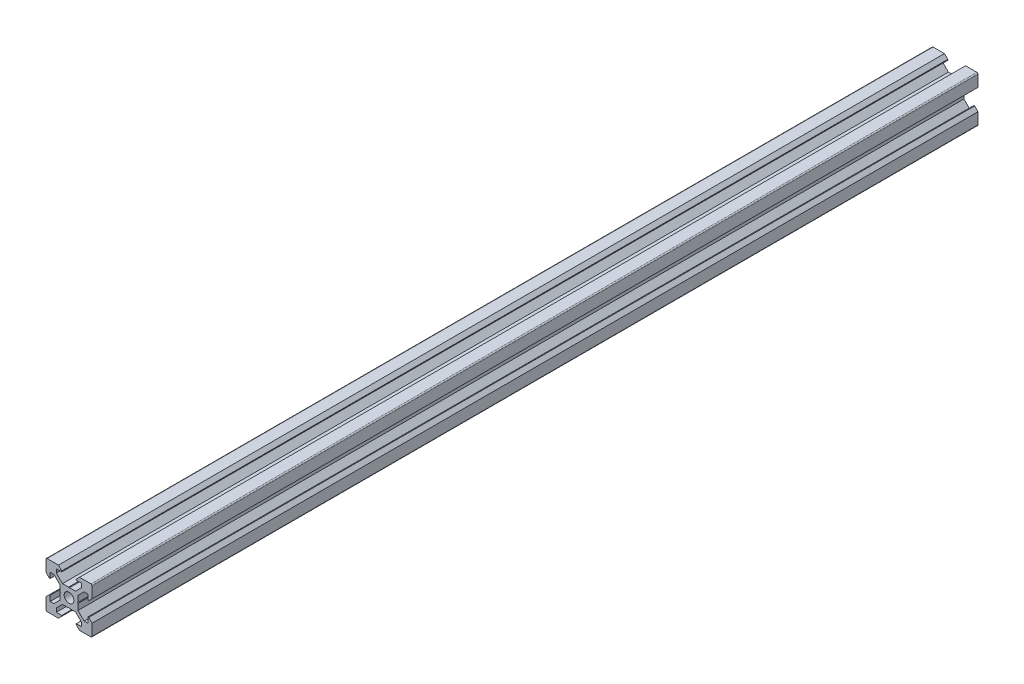
SolidWorks part; units mm, degrees
material "6061-T6 (SS)"
ref_plane "Front Plane" through (0, 0, 0) normal (0, 0, 1) x (1, 0, 0)
ref_plane "Top Plane" through (0, 0, 0) normal (0, 1, 0) x (1, 0, 0)
ref_plane "Right Plane" through (0, 0, 0) normal (1, 0, 0) x (0, 0, -1)
sketch "Sketch1" plane through (0, 0, 0) normal (0, 0, 1) x (1, 0, 0)
  line L1 (9.5, -10) -> (-9.5, -10)
  line L2 (10, -9.5) -> (10, 9.5)
  line L3 (9.5, 10) -> (-9.5, 10)
  line L4 (-10, -9.5) -> (-10, 9.5)
  line L5 (10, -10) -> (-10, 10) construction
  line L6 (10, 10) -> (-10, -10) construction
  circle A0 centre (0, 0) radius 2.1
  arc A1 (-9.5, 10) -> (-10, 9.5) centre (-9.5, 9.5) ccw
  arc A2 (10, 9.5) -> (9.5, 10) centre (9.5, 9.5) ccw
  arc A3 (9.5, -10) -> (10, -9.5) centre (9.5, -9.5) ccw
  arc A4 (-9.5, -10) -> (-10, -9.5) centre (-9.5, -9.5) cw
  point P0 (0, 0)
  line B0 (0, 0) -> (0, 10) construction
  line B1 (0, 3.69) -> (-0.21, 3.9)
  line B2 (-0.21, 3.9) -> (-2.8393, 3.9)
  line B3 (-2.8393, 3.9) -> (-5.5, 6.5607)
  line B4 (-5.5, 6.5607) -> (-5.5, 8.2)
  line B5 (-5.5, 8.2) -> (-3.125, 8.2)
  line B6 (-3.125, 8.2) -> (-3.125, 8.545)
  line B7 (-3.125, 8.545) -> (-4.58, 10)
  line B8 (-4.58, 10) -> (4.58, 10)
  line B9 (0, 0) -> (-5.9132, 5.9132) construction
  line B10 (3.125, 8.545) -> (4.58, 10)
  line B11 (3.125, 8.2) -> (3.125, 8.545)
  line B12 (5.5, 8.2) -> (3.125, 8.2)
  line B13 (5.5, 6.5607) -> (5.5, 8.2)
  line B14 (2.8393, 3.9) -> (5.5, 6.5607)
  line B15 (0.21, 3.9) -> (2.8393, 3.9)
  line B16 (0, 3.69) -> (0.21, 3.9)
  line B17 (0, 0) -> (-10, 0) construction
  line B18 (-3.69, 0) -> (-3.9, -0.21)
  line B19 (-3.9, -0.21) -> (-3.9, -2.8393)
  line B20 (-3.9, -2.8393) -> (-6.5607, -5.5)
  line B21 (-6.5607, -5.5) -> (-8.2, -5.5)
  line B22 (-8.2, -5.5) -> (-8.2, -3.125)
  line B23 (-8.2, -3.125) -> (-8.545, -3.125)
  line B24 (-8.545, -3.125) -> (-10, -4.58)
  line B25 (-10, -4.58) -> (-10, 4.58)
  line B26 (0, 0) -> (-5.9132, -5.9132) construction
  line B27 (-8.545, 3.125) -> (-10, 4.58)
  line B28 (-8.2, 3.125) -> (-8.545, 3.125)
  line B29 (-8.2, 5.5) -> (-8.2, 3.125)
  line B30 (-6.5607, 5.5) -> (-8.2, 5.5)
  line B31 (-3.9, 2.8393) -> (-6.5607, 5.5)
  line B32 (-3.9, 0.21) -> (-3.9, 2.8393)
  line B33 (-3.69, 0) -> (-3.9, 0.21)
  line B34 (0, 0) -> (0, -10) construction
  line B35 (0, -3.69) -> (0.21, -3.9)
  line B36 (0.21, -3.9) -> (2.8393, -3.9)
  line B37 (2.8393, -3.9) -> (5.5, -6.5607)
  line B38 (5.5, -6.5607) -> (5.5, -8.2)
  line B39 (5.5, -8.2) -> (3.125, -8.2)
  line B40 (3.125, -8.2) -> (3.125, -8.545)
  line B41 (3.125, -8.545) -> (4.58, -10)
  line B42 (4.58, -10) -> (-4.58, -10)
  line B43 (0, 0) -> (5.9132, -5.9132) construction
  line B44 (-3.125, -8.545) -> (-4.58, -10)
  line B45 (-3.125, -8.2) -> (-3.125, -8.545)
  line B46 (-5.5, -8.2) -> (-3.125, -8.2)
  line B47 (-5.5, -6.5607) -> (-5.5, -8.2)
  line B48 (-2.8393, -3.9) -> (-5.5, -6.5607)
  line B49 (-0.21, -3.9) -> (-2.8393, -3.9)
  line B50 (0, -3.69) -> (-0.21, -3.9)
  line B51 (0, 0) -> (10, 0) construction
  line B52 (3.69, 0) -> (3.9, 0.21)
  line B53 (3.9, 0.21) -> (3.9, 2.8393)
  line B54 (3.9, 2.8393) -> (6.5607, 5.5)
  line B55 (6.5607, 5.5) -> (8.2, 5.5)
  line B56 (8.2, 5.5) -> (8.2, 3.125)
  line B57 (8.2, 3.125) -> (8.545, 3.125)
  line B58 (8.545, 3.125) -> (10, 4.58)
  line B59 (10, 4.58) -> (10, -4.58)
  line B60 (0, 0) -> (5.9132, 5.9132) construction
  line B61 (8.545, -3.125) -> (10, -4.58)
  line B62 (8.2, -3.125) -> (8.545, -3.125)
  line B63 (8.2, -5.5) -> (8.2, -3.125)
  line B64 (6.5607, -5.5) -> (8.2, -5.5)
  line B65 (3.9, -2.8393) -> (6.5607, -5.5)
  line B66 (3.9, -0.21) -> (3.9, -2.8393)
  line B67 (3.69, 0) -> (3.9, -0.21)
  dimension "D1" = 4.2
  dimension "D3" = 0.5
  dimension "D2" = 20
sketch_block_instance "V Slot 1-4"
sketch_block "V Slot 1" parameters "D1"=10, "D2"=11, "D3"=4.3, "D4"=1.8, "D5"=0.21, "D6"=45, "D7"=9.16, "D8"=1.5, "D9"=6.25
sketch_block_instance "V Slot 1-5"
sketch_block_instance "V Slot 1-6"
sketch_block_instance "V Slot 1-7"
extrude "Boss-Extrude1" add sketch "Sketch1" along normal blind 385 contours B67 B52 B53 B54 B55 B56 B57 B58 L2 A2 L3 B10 B11 B12 B13 B14 B15 B16 B1 B2 B3 B4 B5 B6 B7 A1 L4 B27 B28 B29 B30 B31 B32 B33 B18 B19 B20 B21 B22 B23 B24 A4 L1 B44 B45 B46 B47 B48 B49
